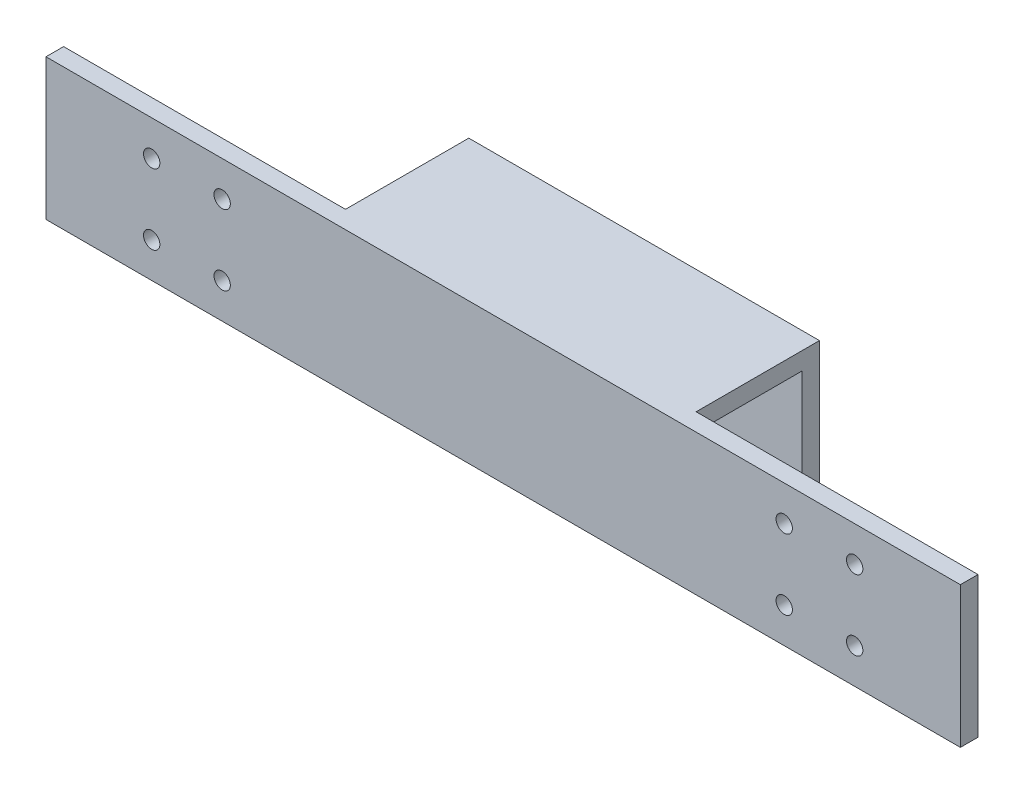
SolidWorks part; units mm, degrees
ref_plane "Front Plane" through (0, 0, 0) normal (0, 0, 1) x (1, 0, 0)
ref_plane "Top Plane" through (0, 0, 0) normal (0, 1, 0) x (1, 0, 0)
ref_plane "Right Plane" through (0, 0, 0) normal (1, 0, 0) x (0, 0, -1)
sketch "Sketch1" plane through (0, 0, 0) normal (1, 0, 0) x (0, 0, -1)
  line L0 (-6.1245, 4.9447) -> (12.9255, 4.9447)
  line L1 (-9.2995, 8.1197) -> (16.1005, 8.1197)
  line L2 (-9.2995, 8.1197) -> (-9.2995, -17.2803)
  line L3 (-9.2995, -17.2803) -> (16.1005, -17.2803)
  line L4 (16.1005, 8.1197) -> (16.1005, -17.2803)
  line L5 (12.9255, 4.9447) -> (12.9255, -14.1053)
  line L6 (-6.1245, -14.1053) -> (12.9255, -14.1053)
  line L7 (-6.1245, 4.9447) -> (-6.1245, -14.1053)
  dimension "D1" = 25.4
  dimension "D2" = 25.4
  dimension "D3" = 3.175
extrude "Boss-Extrude1" add sketch "Sketch1" along normal blind 164.8
sketch "Sketch2" plane through (164.8, 0, 0) normal (1, 0, 0) x (0, 0, -1)
  line L0 (-9.2995, -17.2803) -> (16.1005, -17.2803) construction
  line L1 (16.1005, 8.1197) -> (-6.1245, 8.1197)
  line L2 (16.1005, 8.1197) -> (16.1005, -17.2803)
  line L3 (16.1005, -17.2803) -> (-6.1245, -17.2803)
  line L4 (-6.1245, 8.1197) -> (-6.1245, -17.2803)
extrude "Cut-Extrude1" cut sketch "Sketch2" against normal blind 50.8
sketch "Sketch3" plane through (0, 0, 0) normal (-1, 0, 0) x (0, 0, 1)
  line L1 (-16.1005, 8.1197) -> (6.1245, 8.1197)
  line L2 (-16.1005, 8.1197) -> (-16.1005, -17.2803)
  line L3 (-16.1005, -17.2803) -> (6.1245, -17.2803)
  line L4 (6.1245, 8.1197) -> (6.1245, -17.2803)
extrude "Cut-Extrude2" cut sketch "Sketch3" against normal blind 50.8
sketch "Sketch4" plane through (0, 0, 9.2995) normal (0, 0, 1) x (1, 0, 0)
  line L0 (0, -4.5803) -> (164.8, -4.5803) construction
  line L1 (0, 8.1197) -> (0, -17.2803) construction
  line L2 (164.8, 8.1197) -> (164.8, -17.2803) construction
  line L3 (82.4, 8.1197) -> (82.4, -17.2803) construction
  line L4 (164.8, 8.1197) -> (0, 8.1197) construction
  line L5 (164.8, -17.2803) -> (0, -17.2803) construction
  line L6 (139.4, 8.1197) -> (139.4, -17.2803) construction
  line L7 (25.4, 8.1197) -> (25.4, -17.2803) construction
  line L8 (50.8, 4.9447) -> (50.8, -14.1053) construction
  line L10 (114, 4.9447) -> (114, -14.1053) construction
  circle A0 centre (19.05, 1.7697) radius 1.4732
  circle A1 centre (31.75, 1.7697) radius 1.4732
  circle A2 centre (31.75, -10.9303) radius 1.4732
  circle A3 centre (19.05, -10.9303) radius 1.4732
  circle A4 centre (145.75, -10.9303) radius 1.4732
  circle A5 centre (133.05, -10.9303) radius 1.4732
  circle A6 centre (133.05, 1.7697) radius 1.4732
  circle A7 centre (145.75, 1.7697) radius 1.4732
  dimension "D5" = 2.9464
  dimension "D1" = 25.4
  dimension "D2" = 25.4
  dimension "D3" = 6.35
  dimension "D4" = 6.35
extrude "Cut-Extrude3" cut sketch "Sketch4" against normal blind 50.8
